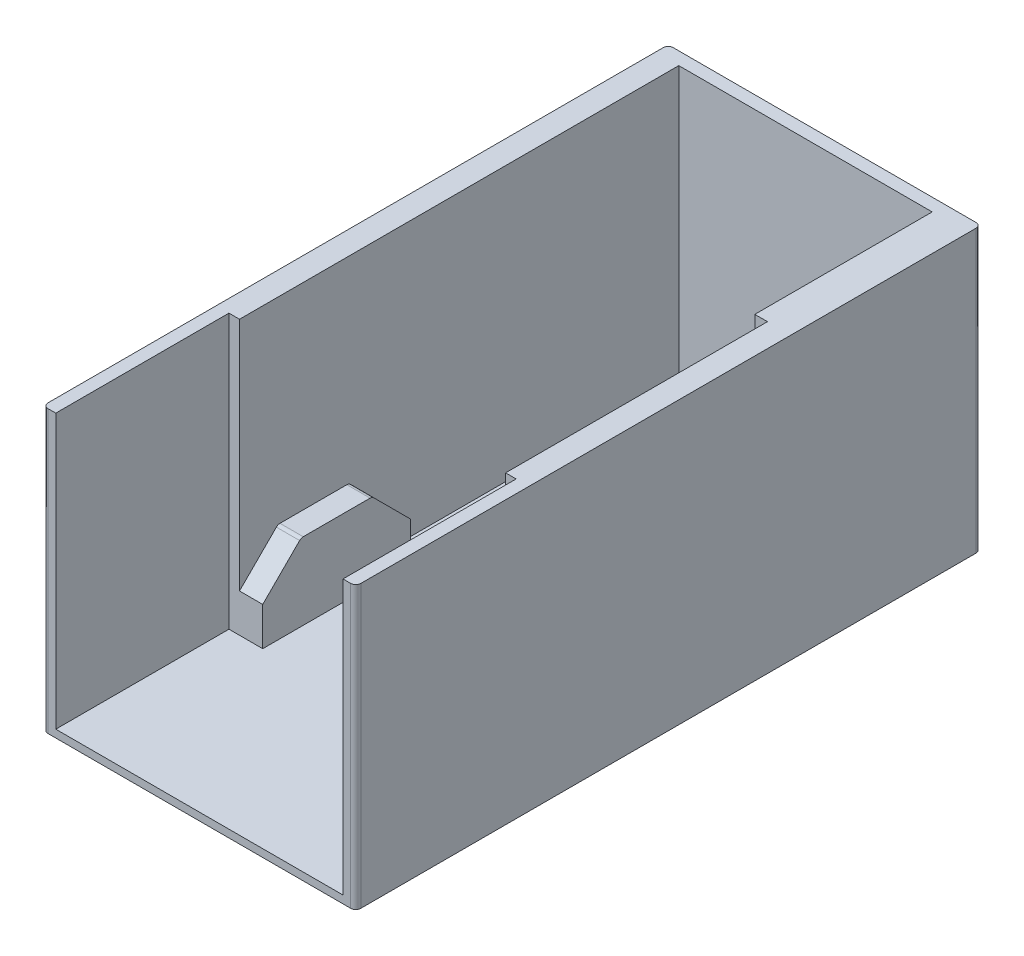
SolidWorks part; units mm, degrees
ref_plane "Front Plane" through (0, 0, 0) normal (0, 0, 1) x (1, 0, 0)
ref_plane "Top Plane" through (0, 0, 0) normal (0, 1, 0) x (1, 0, 0)
ref_plane "Right Plane" through (0, 0, 0) normal (1, 0, 0) x (0, 0, -1)
sketch "Sketch1" plane through (0, 0, 0) normal (0, 1, 0) x (1, 0, 0)
  line L0 (0, 0) -> (0, 2095.5) construction
  line L1 (-863.6, -520.7) -> (863.6, -520.7)
  line L2 (-863.6, -520.7) -> (-863.6, 520.7)
  line L3 (-863.6, 520.7) -> (863.6, 520.7)
  line L4 (863.6, -520.7) -> (863.6, 520.7)
  line L5 (-863.6, -520.7) -> (863.6, 520.7) construction
  line L6 (-863.6, 520.7) -> (863.6, -520.7) construction
  line L7 (-660.4, 520.7) -> (660.4, 520.7)
  line L8 (-660.4, 520.7) -> (-660.4, 1409.7)
  line L9 (-660.4, 1409.7) -> (660.4, 1409.7)
  line L10 (660.4, 520.7) -> (660.4, 1409.7)
  line L12 (-800.1, 1409.7) -> (800.1, 1409.7)
  line L13 (-800.1, 1409.7) -> (-800.1, 2095.5)
  line L14 (-800.1, 2095.5) -> (800.1, 2095.5)
  line L15 (800.1, 1409.7) -> (800.1, 2095.5)
  line L16 (-800.1, 2095.5) -> (723.9, 2095.5)
  line L17 (-800.1, 2095.5) -> (-800.1, 3162.3)
  line L18 (-800.1, 3162.3) -> (723.9, 3162.3)
  line L19 (723.9, 2095.5) -> (723.9, 3162.3)
  point P0 (0, 0)
  point P10 (0, 1409.7)
  point P13 (0, 2095.5)
  dimension "D1" = 1727.2
  dimension "D2" = 1041.4
  dimension "D3" = 1320.8
  dimension "D4" = 889
  dimension "D5" = 1600.2
  dimension "D6" = 685.8
  dimension "D7" = 1524
  dimension "D8" = 1066.8
sketch "Sketch2" plane through (0, 0, 0) normal (0, 1, 0) x (1, 0, 0)
  line L0 (-275, 3062.3) -> (-275, 3012.3) construction
  line L1 (-450, 3012.3) -> (-100, 3012.3)
  line L2 (-450, 3012.3) -> (-450, 2512.3)
  line L3 (-450, 2512.3) -> (-100, 2512.3)
  line L4 (-100, 3012.3) -> (-100, 2512.3)
  line L5 (-500, 3062.3) -> (-50, 3062.3)
  line L6 (-500, 3062.3) -> (-500, 2462.3)
  line L7 (-500, 2462.3) -> (-50, 2462.3)
  line L8 (-50, 3062.3) -> (-50, 2462.3)
  line L9 (-450, 2762.3) -> (-500, 2762.3) construction
  line L10 (100, 3012.3) -> (100, 2512.3)
  line L11 (100, 3012.3) -> (450, 3012.3)
  line L12 (450, 3012.3) -> (450, 2512.3)
  line L13 (100, 2512.3) -> (450, 2512.3)
  line L14 (50, 3062.3) -> (50, 2462.3)
  line L15 (50, 3062.3) -> (500, 3062.3)
  line L16 (500, 3062.3) -> (500, 2462.3)
  line L17 (50, 2462.3) -> (500, 2462.3)
  line L18 (100, 2312.3) -> (100, 1812.3)
  line L19 (100, 2312.3) -> (450, 2312.3)
  line L20 (450, 2312.3) -> (450, 1812.3)
  line L21 (100, 1812.3) -> (450, 1812.3)
  line L22 (50, 2362.3) -> (50, 1762.3)
  line L23 (50, 2362.3) -> (500, 2362.3)
  line L24 (500, 2362.3) -> (500, 1762.3)
  line L25 (50, 1762.3) -> (500, 1762.3)
  line L26 (100, 1612.3) -> (100, 1112.3)
  line L27 (100, 1612.3) -> (450, 1612.3)
  line L28 (450, 1612.3) -> (450, 1112.3)
  line L29 (100, 1112.3) -> (450, 1112.3)
  line L30 (50, 1662.3) -> (50, 1062.3)
  line L31 (50, 1662.3) -> (500, 1662.3)
  line L32 (500, 1662.3) -> (500, 1062.3)
  line L33 (50, 1062.3) -> (500, 1062.3)
  line L34 (100, 912.3) -> (100, 412.3)
  line L35 (100, 912.3) -> (450, 912.3)
  line L36 (450, 912.3) -> (450, 412.3)
  line L37 (100, 412.3) -> (450, 412.3)
  line L38 (50, 962.3) -> (50, 362.3)
  line L39 (50, 962.3) -> (500, 962.3)
  line L40 (500, 962.3) -> (500, 362.3)
  line L41 (50, 362.3) -> (500, 362.3)
  line L42 (-450, 2312.3) -> (-450, 1812.3)
  line L43 (-450, 2312.3) -> (-100, 2312.3)
  line L44 (-100, 2312.3) -> (-100, 1812.3)
  line L45 (-450, 1812.3) -> (-100, 1812.3)
  line L46 (-500, 2362.3) -> (-500, 1762.3)
  line L47 (-500, 2362.3) -> (-50, 2362.3)
  line L48 (-50, 2362.3) -> (-50, 1762.3)
  line L49 (-500, 1762.3) -> (-50, 1762.3)
  line L50 (-450, 1612.3) -> (-450, 1112.3)
  line L51 (-450, 1612.3) -> (-100, 1612.3)
  line L52 (-100, 1612.3) -> (-100, 1112.3)
  line L53 (-450, 1112.3) -> (-100, 1112.3)
  line L54 (-500, 1662.3) -> (-500, 1062.3)
  line L55 (-500, 1662.3) -> (-50, 1662.3)
  line L56 (-50, 1662.3) -> (-50, 1062.3)
  line L57 (-500, 1062.3) -> (-50, 1062.3)
  line L58 (-450, 912.3) -> (-450, 412.3)
  line L59 (-450, 912.3) -> (-100, 912.3)
  line L60 (-100, 912.3) -> (-100, 412.3)
  line L61 (-450, 412.3) -> (-100, 412.3)
  line L62 (-500, 962.3) -> (-500, 362.3)
  line L63 (-500, 962.3) -> (-50, 962.3)
  line L64 (-50, 962.3) -> (-50, 362.3)
  line L65 (-500, 362.3) -> (-50, 362.3)
  line L66 (-450, 3012.3) -> (100, 3012.3) construction
  line L67 (-450, 3012.3) -> (-450, 2312.3) construction
  line L68 (-50, 3062.3) -> (50, 3062.3) construction
  line L69 (0, 3062.3) -> (0, 2095.5) construction
  line L70 (-500, 2462.3) -> (-500, 2362.3)
  line L71 (-550, 3112.3) -> (550, 3112.3)
  line L72 (-550, 3112.3) -> (-550, 312.3)
  line L73 (-550, 312.3) -> (550, 312.3)
  line L74 (550, 3112.3) -> (550, 312.3)
  line L75 (-800.1, 3162.3) -> (723.9, 3162.3) construction
  dimension "D1" = 350
  dimension "D2" = 500
  dimension "D3" = 450
  dimension "D4" = 600
  dimension "D5" = 2
  dimension "D7" = 90
  dimension "D8" = 550
  dimension "D9" = 50
  dimension "D10" = 50
  dimension "D11" = 50
  dimension "D12" = 50
  dimension "D13" = 100
  dimension "D14" = 50
  dimension "D6" = 4
sketch "Resized Everything" plane through (0, 0, 0) normal (0, 1, 0) x (1, 0, 0)
  line L85 (-790.321, 2977.388) -> (-697.865, 2977.388)
  line L86 (-697.865, 2977.388) -> (-697.865, 3039.618)
  line L87 (-790.321, 3039.618) -> (-697.865, 3039.618)
  line L88 (-790.321, 2977.388) -> (-790.321, 3039.618)
  line L89 (-804.545, 2904.49) -> (-683.641, 2904.49)
  line L90 (-683.641, 2904.49) -> (-683.641, 2977.388)
  line L91 (-804.545, 2977.388) -> (-683.641, 2977.388)
  line L92 (-804.545, 2904.49) -> (-804.545, 2977.388)
  line L93 (-800.1, 3039.618) -> (-800.1, 3087.624)
  line L94 (-800.1, 3039.618) -> (-688.086, 3039.618)
  line L95 (-688.086, 3039.618) -> (-688.086, 3087.624)
  line L96 (-800.1, 3087.624) -> (-688.086, 3087.624)
  line L97 (-800.1, 3087.624) -> (-693.42, 3087.624)
  line L98 (-693.42, 3087.624) -> (-693.42, 3162.3)
  line L99 (-800.1, 3162.3) -> (-693.42, 3162.3)
  line L100 (-800.1, 3087.624) -> (-800.1, 3162.3)
  line L101 (-779.093, 3113.3) -> (-779.093, 3106.3)
  line L102 (-779.093, 3113.3) -> (-747.593, 3113.3)
  line L103 (-747.593, 3155.3) -> (-747.593, 3113.3)
  line L104 (-779.093, 3155.3) -> (-747.593, 3155.3)
  line L105 (-779.093, 3155.3) -> (-779.093, 3113.3)
  line L106 (-775.593, 3151.8) -> (-751.093, 3151.8)
  line L107 (-751.093, 3151.8) -> (-751.093, 3116.8)
  line L108 (-775.593, 3116.8) -> (-751.093, 3116.8)
  line L109 (-775.593, 3151.8) -> (-775.593, 3116.8)
  line L110 (-740.593, 3106.3) -> (-740.593, 3064.3)
  line L111 (-740.593, 3064.3) -> (-709.093, 3064.3)
  line L112 (-709.093, 3106.3) -> (-709.093, 3064.3)
  line L113 (-740.593, 3106.3) -> (-709.093, 3106.3)
  line L114 (-737.093, 3102.8) -> (-737.093, 3067.8)
  line L115 (-737.093, 3067.8) -> (-712.593, 3067.8)
  line L116 (-712.593, 3102.8) -> (-712.593, 3067.8)
  line L117 (-737.093, 3102.8) -> (-712.593, 3102.8)
  line L118 (-740.593, 3155.3) -> (-740.593, 3113.3)
  line L119 (-740.593, 3113.3) -> (-709.093, 3113.3)
  line L120 (-709.093, 3155.3) -> (-709.093, 3113.3)
  line L121 (-740.593, 3155.3) -> (-709.093, 3155.3)
  line L122 (-737.093, 3151.8) -> (-737.093, 3116.8)
  line L123 (-737.093, 3151.8) -> (-712.593, 3151.8)
  line L124 (-712.593, 3151.8) -> (-712.593, 3116.8)
  line L125 (-737.093, 3116.8) -> (-712.593, 3116.8)
  line L126 (-740.593, 3008.3) -> (-740.593, 2966.3)
  line L127 (-740.593, 2966.3) -> (-709.093, 2966.3)
  line L128 (-709.093, 3008.3) -> (-709.093, 2966.3)
  line L129 (-740.593, 3008.3) -> (-709.093, 3008.3)
  line L130 (-737.093, 3004.8) -> (-737.093, 2969.8)
  line L131 (-737.093, 2969.8) -> (-712.593, 2969.8)
  line L132 (-712.593, 3004.8) -> (-712.593, 2969.8)
  line L133 (-737.093, 3004.8) -> (-712.593, 3004.8)
  line L134 (-740.593, 3057.3) -> (-740.593, 3015.3)
  line L135 (-740.593, 3015.3) -> (-709.093, 3015.3)
  line L136 (-709.093, 3057.3) -> (-709.093, 3015.3)
  line L137 (-740.593, 3057.3) -> (-709.093, 3057.3)
  line L138 (-737.093, 3053.8) -> (-737.093, 3018.8)
  line L139 (-737.093, 3053.8) -> (-712.593, 3053.8)
  line L140 (-712.593, 3053.8) -> (-712.593, 3018.8)
  line L141 (-737.093, 3018.8) -> (-712.593, 3018.8)
  line L142 (-779.093, 3057.3) -> (-779.093, 3015.3)
  line L143 (-779.093, 3015.3) -> (-747.593, 3015.3)
  line L144 (-747.593, 3057.3) -> (-747.593, 3015.3)
  line L145 (-779.093, 3057.3) -> (-747.593, 3057.3)
  line L146 (-775.593, 3053.8) -> (-775.593, 3018.8)
  line L147 (-775.593, 3018.8) -> (-751.093, 3018.8)
  line L148 (-751.093, 3053.8) -> (-751.093, 3018.8)
  line L149 (-775.593, 3053.8) -> (-751.093, 3053.8)
  line L150 (-779.093, 3106.3) -> (-779.093, 3064.3)
  line L151 (-779.093, 3064.3) -> (-747.593, 3064.3)
  line L152 (-747.593, 3106.3) -> (-747.593, 3064.3)
  line L153 (-779.093, 3106.3) -> (-747.593, 3106.3)
  line L154 (-775.593, 3102.8) -> (-775.593, 3067.8)
  line L155 (-775.593, 3102.8) -> (-751.093, 3102.8)
  line L156 (-751.093, 3102.8) -> (-751.093, 3067.8)
  line L157 (-775.593, 3067.8) -> (-751.093, 3067.8)
  line L158 (-782.593, 3158.8) -> (-705.593, 3158.8)
  line L159 (-705.593, 3158.8) -> (-705.593, 2962.8)
  line L160 (-782.593, 2962.8) -> (-705.593, 2962.8)
  line L161 (-782.593, 3158.8) -> (-782.593, 2962.8)
  line L162 (-779.093, 3008.3) -> (-779.093, 2966.3)
  line L163 (-779.093, 2966.3) -> (-747.593, 2966.3)
  line L164 (-747.593, 3008.3) -> (-747.593, 2966.3)
  line L165 (-779.093, 3008.3) -> (-747.593, 3008.3)
  line L166 (-775.593, 3004.8) -> (-775.593, 2969.8)
  line L167 (-775.593, 3004.8) -> (-751.093, 3004.8)
  line L168 (-751.093, 3004.8) -> (-751.093, 2969.8)
  line L169 (-775.593, 2969.8) -> (-751.093, 2969.8)
sketch "Sketch6" plane through (0, 0, 0) normal (0, 1, 0) x (1, 0, 0)
  line L0 (-800.1, 3162.3) -> (723.9, 3162.3) construction
  line L1 (-748.0935, 2917.905) -> (-748.0935, 3167.3) construction
  line L2 (-809.2275, 2917.905) -> (-686.9595, 2917.905)
  line L3 (-686.9595, 2917.905) -> (-686.9595, 3167.3)
  line L4 (-686.9595, 3167.3) -> (-809.2275, 3167.3)
  line L5 (-696.087, 3048.381) -> (-696.087, 2990.596)
  line L6 (-800.1, 3048.381) -> (-800.1, 2990.596)
  line L7 (-809.2275, 2917.905) -> (-809.2275, 3167.3)
  line L8 (-701.04, 3162.3) -> (-696.087, 3162.3)
  line L9 (-696.087, 3162.3) -> (-696.087, 3092.958)
  line L10 (-804.2275, 2922.905) -> (-809.2275, 2922.905)
  line L11 (-691.9595, 2922.905) -> (-686.9595, 2922.905)
  line L16 (-791.0195, 2990.596) -> (-705.1675, 2990.596)
  line L17 (-705.1675, 2990.596) -> (-705.1675, 3048.381)
  line L18 (-791.0195, 3048.381) -> (-705.1675, 3048.381)
  line L19 (-791.0195, 2990.596) -> (-791.0195, 3048.381)
  line L20 (-804.2275, 2922.905) -> (-691.9595, 2922.905)
  line L21 (-691.9595, 2922.905) -> (-691.9595, 2990.596)
  line L22 (-804.2275, 2990.596) -> (-691.9595, 2990.596)
  line L23 (-804.2275, 2922.905) -> (-804.2275, 2990.596)
  line L24 (-800.1, 3048.381) -> (-800.1, 3092.958)
  line L25 (-800.1, 3048.381) -> (-696.087, 3048.381)
  line L26 (-696.087, 3048.381) -> (-696.087, 3092.958)
  line L27 (-800.1, 3092.958) -> (-696.087, 3092.958)
  line L28 (-800.1, 3092.958) -> (-701.04, 3092.958)
  line L29 (-701.04, 3092.958) -> (-701.04, 3162.3)
  line L30 (-800.1, 3162.3) -> (-701.04, 3162.3)
  line L31 (-800.1, 3092.958) -> (-800.1, 3162.3)
  point P3 (-748.0935, 2922.905)
  dimension "D1" = 239.395
  dimension "D2" = 5
  dimension "D3" = 5
  dimension "D4" = 5
extrude "Boss-Extrude1" add sketch "Sketch6" along normal blind 107 contours L2 L1 L20 L23 L22 L6 L24 L31 L30 L4 L7 | L1 L2 L3 L4 L30 L29 L27 L26 L5 L22 L21 L20 | L29 L27 L9 L8
sketch "Sketch7" plane through (0, 0, 0) normal (0, -1, 0) x (1, 0, 0)
  line L0 (-800.1, -3048.381) -> (-800.1, -2990.596) construction
  line L1 (-696.087, -3048.381) -> (-696.087, -2990.596) construction
  line L2 (-800.1, -3048.381) -> (-800.1, -3092.958) construction
  line L3 (-800.1, -3092.958) -> (-696.087, -3092.958) construction
  line L4 (-800.1, -3092.958) -> (-701.04, -3092.958) construction
  line L5 (-701.04, -3092.958) -> (-701.04, -3162.3) construction
  line L6 (-800.1, -3162.3) -> (-701.04, -3162.3) construction
  line L7 (-800.1, -3092.958) -> (-800.1, -3162.3) construction
  line L8 (-701.04, -3162.3) -> (-696.087, -3162.3) construction
  line L9 (-696.087, -3162.3) -> (-696.087, -3092.958) construction
  line L10 (-696.087, -3048.381) -> (-696.087, -3092.958) construction
  line L11 (-800.1, -3048.381) -> (-696.087, -3048.381) construction
  line L12 (-809.2275, -2917.905) -> (-686.9595, -2917.905) construction
  line L13 (-686.9595, -2917.905) -> (-686.9595, -3167.3) construction
  line L14 (-686.9595, -3167.3) -> (-809.2275, -3167.3) construction
  line L15 (-809.2275, -2917.905) -> (-809.2275, -3167.3) construction
  line L16 (-804.2275, -2922.905) -> (-691.9595, -2922.905) construction
  line L17 (-691.9595, -2922.905) -> (-691.9595, -2990.596) construction
  line L18 (-804.2275, -2990.596) -> (-691.9595, -2990.596) construction
  line L19 (-804.2275, -2922.905) -> (-804.2275, -2990.596) construction
  line L20 (-705.1675, -2990.596) -> (-705.1675, -3048.381) construction
  line L21 (-791.0195, -3048.381) -> (-705.1675, -3048.381) construction
  line L22 (-791.0195, -2990.596) -> (-791.0195, -3048.381) construction
  line L23 (-791.0195, -2990.596) -> (-705.1675, -2990.596) construction
  line L24 (-800.1, -3048.381) -> (-800.1, -2990.596)
  line L25 (-696.087, -3048.381) -> (-696.087, -2990.596)
  line L26 (-800.1, -3048.381) -> (-800.1, -3092.958)
  line L27 (-800.1, -3092.958) -> (-696.087, -3092.958)
  line L28 (-800.1, -3092.958) -> (-701.04, -3092.958)
  line L29 (-701.04, -3092.958) -> (-701.04, -3162.3)
  line L30 (-800.1, -3162.3) -> (-701.04, -3162.3)
  line L31 (-800.1, -3092.958) -> (-800.1, -3162.3)
  line L32 (-701.04, -3162.3) -> (-696.087, -3162.3)
  line L33 (-696.087, -3162.3) -> (-696.087, -3092.958)
  line L34 (-696.087, -3048.381) -> (-696.087, -3092.958)
  line L35 (-800.1, -3048.381) -> (-696.087, -3048.381)
  line L36 (-809.2275, -2917.905) -> (-686.9595, -2917.905)
  line L37 (-686.9595, -2917.905) -> (-686.9595, -3167.3)
  line L38 (-686.9595, -3167.3) -> (-809.2275, -3167.3)
  line L39 (-809.2275, -2917.905) -> (-809.2275, -3167.3)
  line L40 (-804.2275, -2922.905) -> (-691.9595, -2922.905)
  line L41 (-691.9595, -2922.905) -> (-691.9595, -2990.596)
  line L42 (-804.2275, -2990.596) -> (-691.9595, -2990.596)
  line L43 (-804.2275, -2922.905) -> (-804.2275, -2990.596)
  line L44 (-705.1675, -2990.596) -> (-705.1675, -3048.381)
  line L45 (-791.0195, -3048.381) -> (-705.1675, -3048.381)
  line L46 (-791.0195, -2990.596) -> (-791.0195, -3048.381)
  line L47 (-791.0195, -2990.596) -> (-705.1675, -2990.596)
extrude "Boss-Extrude2" add sketch "Sketch7" along normal blind 3 contours L39 L38 L37 L36
sketch "Sketch8" plane through (0, 0, 0) normal (0, 1, 0) x (1, 0, 0)
  line L0 (-691.9595, 2922.905) -> (-686.9595, 2922.905) construction
  line L1 (-804.2275, 2922.905) -> (-809.2275, 2922.905) construction
  line L2 (-800.1, 3048.381) -> (-800.1, 2990.596) construction
  line L3 (-696.087, 3048.381) -> (-696.087, 2990.596) construction
  line L4 (-800.1, 3048.381) -> (-800.1, 3092.958) construction
  line L5 (-800.1, 3092.958) -> (-696.087, 3092.958) construction
  line L6 (-800.1, 3092.958) -> (-701.04, 3092.958) construction
  line L7 (-701.04, 3092.958) -> (-701.04, 3162.3) construction
  line L8 (-800.1, 3162.3) -> (-701.04, 3162.3) construction
  line L9 (-800.1, 3092.958) -> (-800.1, 3162.3) construction
  line L10 (-804.2275, 2922.905) -> (-691.9595, 2922.905) construction
  line L11 (-691.9595, 2922.905) -> (-691.9595, 2990.596) construction
  line L12 (-804.2275, 2990.596) -> (-691.9595, 2990.596) construction
  line L13 (-804.2275, 2922.905) -> (-804.2275, 2990.596) construction
  line L14 (-701.04, 3162.3) -> (-696.087, 3162.3) construction
  line L15 (-696.087, 3162.3) -> (-696.087, 3092.958) construction
  line L16 (-696.087, 3048.381) -> (-696.087, 3092.958) construction
  line L17 (-800.1, 3048.381) -> (-696.087, 3048.381) construction
  line L18 (-809.2275, 2917.905) -> (-686.9595, 2917.905) construction
  line L19 (-686.9595, 2917.905) -> (-686.9595, 3167.3) construction
  line L20 (-686.9595, 3167.3) -> (-809.2275, 3167.3) construction
  line L21 (-809.2275, 2917.905) -> (-809.2275, 3167.3) construction
  line L22 (-705.1675, 2990.596) -> (-705.1675, 3048.381) construction
  line L23 (-791.0195, 3048.381) -> (-705.1675, 3048.381) construction
  line L24 (-791.0195, 2990.596) -> (-791.0195, 3048.381) construction
  line L25 (-791.0195, 2990.596) -> (-705.1675, 2990.596) construction
  line L26 (-691.9595, 2922.905) -> (-686.9595, 2922.905)
  line L27 (-804.2275, 2922.905) -> (-809.2275, 2922.905)
  line L28 (-800.1, 3048.381) -> (-800.1, 2990.596)
  line L29 (-696.087, 3048.381) -> (-696.087, 2990.596)
  line L30 (-800.1, 3048.381) -> (-800.1, 3092.958)
  line L31 (-800.1, 3092.958) -> (-696.087, 3092.958)
  line L32 (-800.1, 3092.958) -> (-701.04, 3092.958)
  line L33 (-701.04, 3092.958) -> (-701.04, 3162.3)
  line L34 (-800.1, 3162.3) -> (-701.04, 3162.3)
  line L35 (-800.1, 3092.958) -> (-800.1, 3162.3)
  line L36 (-804.2275, 2922.905) -> (-691.9595, 2922.905)
  line L37 (-691.9595, 2922.905) -> (-691.9595, 2990.596)
  line L38 (-804.2275, 2990.596) -> (-691.9595, 2990.596)
  line L39 (-804.2275, 2922.905) -> (-804.2275, 2990.596)
  line L40 (-701.04, 3162.3) -> (-696.087, 3162.3)
  line L41 (-696.087, 3162.3) -> (-696.087, 3092.958)
  line L42 (-696.087, 3048.381) -> (-696.087, 3092.958)
  line L43 (-800.1, 3048.381) -> (-696.087, 3048.381)
  line L44 (-809.2275, 2917.905) -> (-686.9595, 2917.905)
  line L45 (-686.9595, 2917.905) -> (-686.9595, 3167.3)
  line L46 (-686.9595, 3167.3) -> (-809.2275, 3167.3)
  line L47 (-809.2275, 2917.905) -> (-809.2275, 3167.3)
  line L48 (-705.1675, 2990.596) -> (-705.1675, 3048.381)
  line L49 (-791.0195, 3048.381) -> (-705.1675, 3048.381)
  line L50 (-791.0195, 2990.596) -> (-791.0195, 3048.381)
  line L51 (-791.0195, 2990.596) -> (-705.1675, 2990.596)
  line M17 (-696.087, 2990.596) -> (-696.087, 3092.958)
  line M21 (-800.1, 3162.3) -> (-800.1, 2990.596)
extrude "Boss-Extrude3" add sketch "Sketch8" along normal blind 30 contours L38 L50 L43 M21 | L48 L38 L43 M17
ref_plane "Plane1" through (-748.0935, 0, 0) normal (1, 0, 0) x (0, 0, -1)
sketch "Sketch9" plane through (-791.0195, 0, 0) normal (1, 0, 0) x (0, 0, -1)
  line L0 (2990.596, 15) -> (3005.596, 30)
  line L1 (3019.4885, 30) -> (3019.4885, 0) construction
  line L2 (3048.381, 15) -> (3033.381, 30)
  line L4 (2990.596, 0) -> (3048.381, 0)
  line L5 (3048.381, 0) -> (3048.381, 30)
  line L6 (3048.381, 30) -> (2990.596, 30)
  line L7 (2990.596, 30) -> (2990.596, 0)
  line L8 (2990.596, 0) -> (3048.381, 0)
  line L9 (3048.381, 0) -> (3048.381, 30)
  line L10 (3048.381, 30) -> (2990.596, 30)
  line L11 (2990.596, 30) -> (2990.596, 0)
  line M8 (3048.381, 0) -> (3048.381, 30)
  line M9 (3048.381, 30) -> (2990.596, 30)
  line M10 (2990.596, 30) -> (2990.596, 0)
  dimension "D2" = 45
  dimension "D1" = 0
extrude "Cut-Extrude1" cut sketch "Sketch9" against normal up to surface (9.0805 mm away) contours L0 M10 M9 | L2 M8 M9 up to face at (-800.1, 45.6667, -3067.0923)
sketch "Sketch10" plane through (-705.1675, 0, 0) normal (-1, 0, 0) x (0, 0, 1)
  line L0 (-3048.381, 15) -> (-3033.381, 30) construction
  line L1 (-2990.596, 15) -> (-3005.596, 30) construction
  line L2 (-3048.381, 15) -> (-3033.381, 30)
  line L3 (-2990.596, 15) -> (-3005.596, 30)
  line L4 (-3048.381, 0) -> (-2990.596, 0)
  line L5 (-3048.381, 30) -> (-3048.381, 0)
  line L6 (-2990.596, 30) -> (-3048.381, 30)
  line L7 (-2990.596, 0) -> (-2990.596, 30)
  line L8 (-3048.381, 0) -> (-2990.596, 0)
  line L9 (-3048.381, 30) -> (-3048.381, 0)
  line L10 (-2990.596, 30) -> (-3048.381, 30)
  line L11 (-2990.596, 0) -> (-2990.596, 30)
  line M6 (-2990.596, 0) -> (-2990.596, 30)
  line M7 (-2990.596, 30) -> (-3048.381, 30)
  line M8 (-3048.381, 30) -> (-3048.381, 0)
  dimension "D1" = 0
extrude "Cut-Extrude2" cut sketch "Sketch10" against normal up to surface (9.0805 mm away) contours L2 M8 M7 | L3 M6 M7 up to face at (-696.087, 45.6667, -3043.9783)
fillet "Fillet1" radius 2 8 edges at (-686.9595, 53.5, -2922.905) (-686.9595, 52, -3167.3) (-809.2275, 52, -3167.3) (-809.2275, 53.5, -2922.905) (-700.6272, 30, -3033.381) (-700.6272, 30, -3005.596) (-795.5598, 30, -3033.381) (-795.5598, 30, -3005.596)
sketch "Sketch11" plane through (0, 0, 0) normal (0, 1, 0) x (-1, 0, 0)
  line L0 (804.2275, -2922.905) -> (691.9595, -2922.905)
  line L18 (791.0195, -3048.381) -> (791.0195, -2990.596)
  line L19 (791.0195, -2990.596) -> (804.2275, -2990.596)
  line L20 (804.2275, -2990.596) -> (804.2275, -2922.905)
  line L21 (804.2275, -2922.905) -> (807.2275, -2922.905)
  line L22 (809.2275, -2924.905) -> (809.2275, -2917.905)
  line L23 (809.2275, -2917.905) -> (686.9595, -2917.905)
  line L24 (686.9595, -2917.905) -> (686.9595, -2924.905)
  line L25 (688.9595, -2922.905) -> (691.9595, -2922.905)
  line L26 (691.9595, -2922.905) -> (691.9595, -2990.596)
  line L27 (691.9595, -2990.596) -> (705.1675, -2990.596)
  line L28 (705.1675, -2990.596) -> (705.1675, -3048.381)
  line L29 (705.1675, -3048.381) -> (696.087, -3048.381)
  line L30 (696.087, -3048.381) -> (696.087, -3092.958)
  line L31 (696.087, -3092.958) -> (701.04, -3092.958)
  line L32 (701.04, -3092.958) -> (701.04, -3162.3)
  line L33 (701.04, -3162.3) -> (800.1, -3162.3)
  line L34 (800.1, -3162.3) -> (800.1, -3048.381)
  line L35 (800.1, -3048.381) -> (791.0195, -3048.381)
  line L36 (791.0195, -3048.381) -> (791.0195, -2990.596)
  line L37 (791.0195, -2990.596) -> (804.2275, -2990.596)
  line L38 (804.2275, -2990.596) -> (804.2275, -2922.905)
  line L39 (804.2275, -2922.905) -> (807.2275, -2922.905)
  line L40 (809.2275, -2924.905) -> (809.2275, -2917.905)
  line L41 (809.2275, -2917.905) -> (686.9595, -2917.905)
  line L42 (686.9595, -2917.905) -> (686.9595, -2924.905)
  line L43 (688.9595, -2922.905) -> (691.9595, -2922.905)
  line L44 (691.9595, -2922.905) -> (691.9595, -2990.596)
  line L45 (691.9595, -2990.596) -> (705.1675, -2990.596)
  line L46 (705.1675, -2990.596) -> (705.1675, -3048.381)
  line L47 (705.1675, -3048.381) -> (696.087, -3048.381)
  line L48 (696.087, -3048.381) -> (696.087, -3092.958)
  line L49 (696.087, -3092.958) -> (701.04, -3092.958)
  line L50 (701.04, -3092.958) -> (701.04, -3162.3)
  line L51 (701.04, -3162.3) -> (800.1, -3162.3)
  line L52 (800.1, -3162.3) -> (800.1, -3048.381)
  line L53 (800.1, -3048.381) -> (791.0195, -3048.381)
  arc A2 (809.2275, -2924.905) -> (807.2275, -2922.905) centre (807.2275, -2924.905) ccw
  arc A3 (688.9595, -2922.905) -> (686.9595, -2924.905) centre (688.9595, -2924.905) ccw
  arc A4 (809.2275, -2924.905) -> (807.2275, -2922.905) centre (807.2275, -2924.905) ccw
  arc A5 (688.9595, -2922.905) -> (686.9595, -2924.905) centre (688.9595, -2924.905) ccw
  line M24 (804.2275, -2922.905) -> (807.2275, -2922.905)
  arc M25 (807.2275, -2922.905) -> (809.2275, -2924.905) centre (807.2275, -2924.905) cw
  line M26 (809.2275, -2924.905) -> (809.2275, -2917.905)
  line M27 (809.2275, -2917.905) -> (686.9595, -2917.905)
  line M28 (686.9595, -2917.905) -> (686.9595, -2924.905)
  arc M29 (686.9595, -2924.905) -> (688.9595, -2922.905) centre (688.9595, -2924.905) cw
  line M30 (688.9595, -2922.905) -> (691.9595, -2922.905)
  dimension "D1" = 0
extrude "Cut-Extrude3" cut sketch "Sketch11" against normal through all contours L0 M24 M25 M26 M27 M28 M29 M30
equation "\"alpha\"= 1"
equation "\"bin_width\"= 0.5"
equation "\"bin_depth\"= 0.35"
equation "\"bin_height\"= 0.35"
